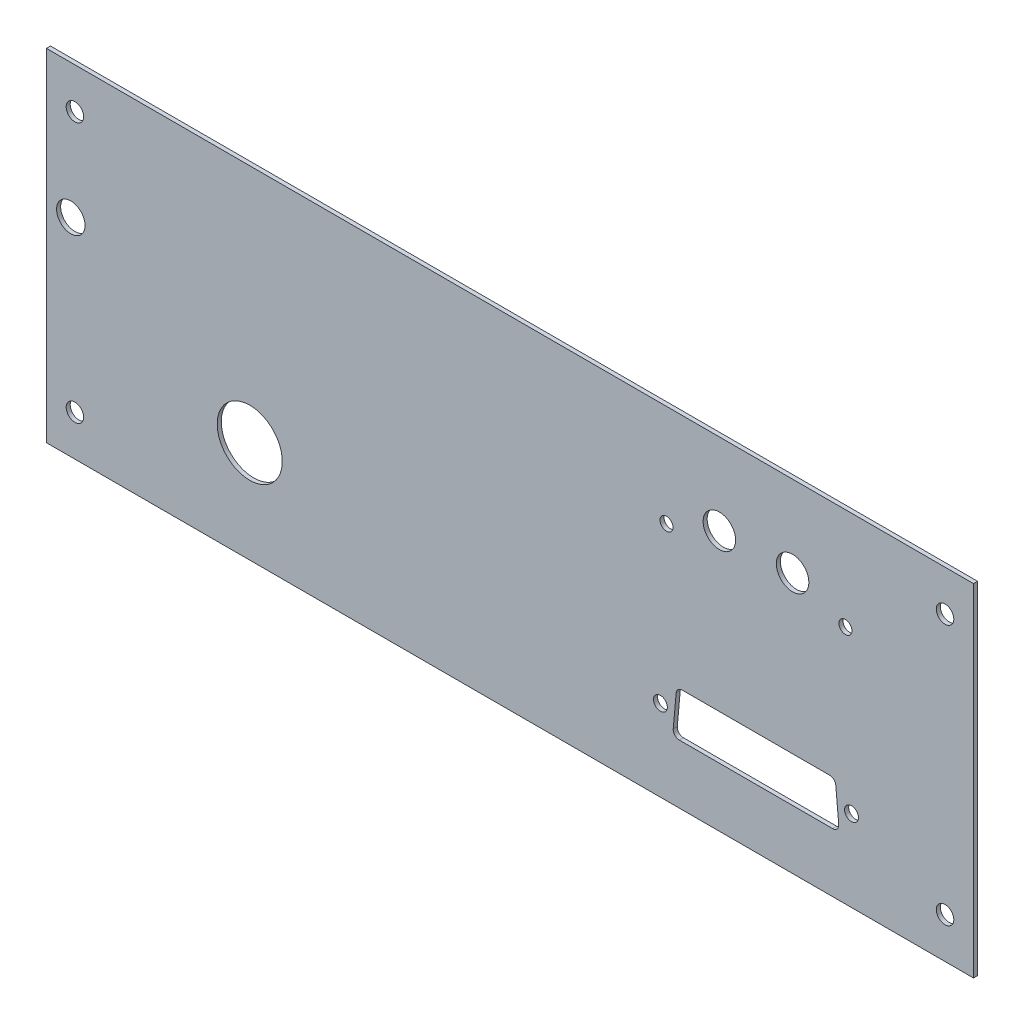
SolidWorks part; units mm, degrees
ref_plane "Спереди" through (0, 0, 0) normal (0, 0, 1) x (1, 0, 0)
ref_plane "Сверху" through (0, 0, 0) normal (0, 1, 0) x (1, 0, 0)
ref_plane "Справа" through (0, 0, 0) normal (1, 0, 0) x (0, 0, -1)
sketch "Эскиз1" plane through (0, 0, 0) normal (0, 0, 1) x (1, 0, 0)
  line L0 (0, 0) -> (58.061, 0) construction
  line L1 (0, 0) -> (0, 47.3035) construction
  line L3 (-114, -42) -> (114, -42)
  line L4 (-114, -42) -> (-114, 42)
  line L5 (-114, 42) -> (114, 42)
  line L6 (114, -42) -> (114, 42)
  circle A8 centre (107, 32) radius 2.15
  circle A9 centre (-107, 32) radius 2.15
  circle A10 centre (-107, -32) radius 2.15
  circle A11 centre (107, -32) radius 2.15
  dimension "D14" = 4.3
  dimension "D15" = 10
  dimension "D16" = 7
  dimension "D1" = 84
  dimension "D2" = 228
extrude "Вытянуть1" add sketch "Эскиз1" along normal blind 1
sketch "Эскиз3" plane through (0, 0, 1) normal (0, 0, 1) x (1, 0, 0)
  line L0 (-47.9981, -22) -> (120.6827, -22) construction
  line L1 (40.1487, -25.8642) -> (40.876, -17.8642)
  line L2 (41.6425, -27.5) -> (79.3575, -27.5)
  line L3 (-114, -42) -> (114, -42) construction
  line L4 (42.3698, -16.5) -> (78.6302, -16.5)
  line L5 (34.3104, 17) -> (86.5925, 17) construction
  line L6 (80.8513, -25.8642) -> (80.124, -17.8642)
  line L7 (60.5, 95.3032) -> (60.5, -77.6913) construction
  line L10 (51.5, 22) -> (68.5193, 22) construction
  line L11 (114, -42) -> (114, 42) construction
  line L12 (114, 42) -> (-114, 42) construction
  circle A0 centre (37, -22) radius 1.7
  circle A1 centre (84, -22) radius 1.7
  arc A2 (41.6425, -27.5) -> (40.1487, -25.8642) centre (41.6425, -26) cw
  arc A3 (42.3698, -16.5) -> (40.876, -17.8642) centre (42.3698, -18) ccw
  arc A4 (80.124, -17.8642) -> (78.6302, -16.5) centre (78.6302, -18) ccw
  arc A5 (79.3575, -27.5) -> (80.8513, -25.8642) centre (79.3575, -26) ccw
  circle A6 centre (38.5, 17) radius 1.6
  circle A7 centre (82.5, 17) radius 1.6
  circle A8 centre (51.5, 22) radius 4
  circle A9 centre (69.5, 22) radius 4
  point P14 (40, -27.5)
  point P17 (41, -16.5)
  point P20 (80, -16.5)
  point P23 (81, -27.5)
  dimension "D4" = 47
  dimension "D5" = 3.4
  dimension "D6" = 1.5
  dimension "D9" = 3.2
  dimension "D11" = 18
  dimension "D12" = 8
  dimension "D13" = 44
  dimension "D14" = 20
  dimension "D8" = 30
  dimension "D1" = 39
  dimension "D2" = 41
  dimension "D3" = 11
  dimension "D7" = 20
  dimension "D10" = 25
extrude "Вырез-Вытянуть1" cut sketch "Эскиз3" against normal blind 10
sketch "Эскиз4" plane through (0, 0, 1) normal (0, 0, 1) x (1, 0, 0)
  line L0 (-114, 42) -> (-114, -42) construction
  line L1 (-114, -42) -> (114, -42) construction
  circle A0 centre (-108, 9) radius 3.5
  circle A1 centre (-64, -17) radius 8
  dimension "D3" = 7
  dimension "D8" = 50
  dimension "D9" = 16
  dimension "D1" = 6
  dimension "D2" = 51
  dimension "D7" = 25
extrude "Вырез-Вытянуть2" cut sketch "Эскиз4" against normal blind 1
